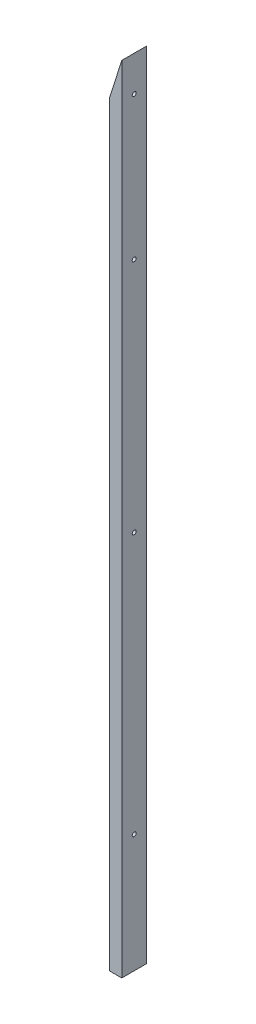
SolidWorks part; units mm, degrees
ref_plane "Спереди" through (0, 0, 0) normal (0, 0, 1) x (1, 0, 0)
ref_plane "Сверху" through (0, 0, 0) normal (0, 1, 0) x (1, 0, 0)
ref_plane "Справа" through (0, 0, 0) normal (1, 0, 0) x (0, 0, -1)
other "Configuration Table"
sketch "Эскиз1" plane through (0, 0, 0) normal (0, 1, 0) x (1, 0, 0)
  line L1 (12.5, 25) -> (-12.5, 25)
  line L2 (12.5, 25) -> (12.5, -25)
  line L3 (12.5, -25) -> (-12.5, -25)
  line L4 (-12.5, 25) -> (-12.5, -25)
  line L5 (12.5, 25) -> (-12.5, -25) construction
  line L6 (12.5, -25) -> (-12.5, 25) construction
  point P0 (0, 0)
extrude "Бобышка-Вытянуть1" add sketch "Эскиз1" along normal blind 1600
sketch "Эскиз2" plane through (0, 0, 25) normal (0, 0, 1) x (1, 0, 0)
  line L0 (-12.5, 1600) -> (-12.5, 1524.17)
  line L1 (-12.5, 1600) -> (-12.5, 0) construction
  line L2 (12.5, 1600) -> (12.5, 1595.7605)
  line L3 (12.5, 1600) -> (12.5, 0) construction
  line L4 (12.5, 1595.7605) -> (-12.5, 1524.17)
  line L5 (12.5, 1600) -> (-12.5, 1600)
sketch "Эскиз4" plane through (12.5, 0, 0) normal (1, 0, 0) x (0, 0, -1)
  line L0 (0, 0) -> (0, 237.5) construction
  line L1 (0, 237.5) -> (0, 762.5) construction
  line L2 (0, 762.5) -> (0, 1237.5) construction
  line L3 (0, 1237.5) -> (0, 1525) construction
  circle A0 centre (0, 237.5) radius 4
  circle A1 centre (0, 762.5) radius 4
  circle A2 centre (0, 1237.5) radius 4
  circle A3 centre (0, 1525) radius 4
extrude "Вырез-Вытянуть4" cut sketch "Эскиз4" against normal blind 550
sketch "Эскиз5" plane through (0, 0, 25) normal (0, 0, 1) x (1, 0, 0)
  line L0 (-12.5, 1600) -> (-12.5, 1517.377)
  line L1 (-12.5, 1600) -> (-12.5, 0) construction
  line L2 (12.5, 1600) -> (12.5, 1596.127)
  line L3 (12.5, 1600) -> (12.5, 0) construction
  line L4 (-12.5, 1600) -> (12.5, 1600)
  line L5 (12.5, 1596.127) -> (-12.5, 1517.377)
extrude "Вырез-Вытянуть5" cut sketch "Эскиз5" against normal blind 60
